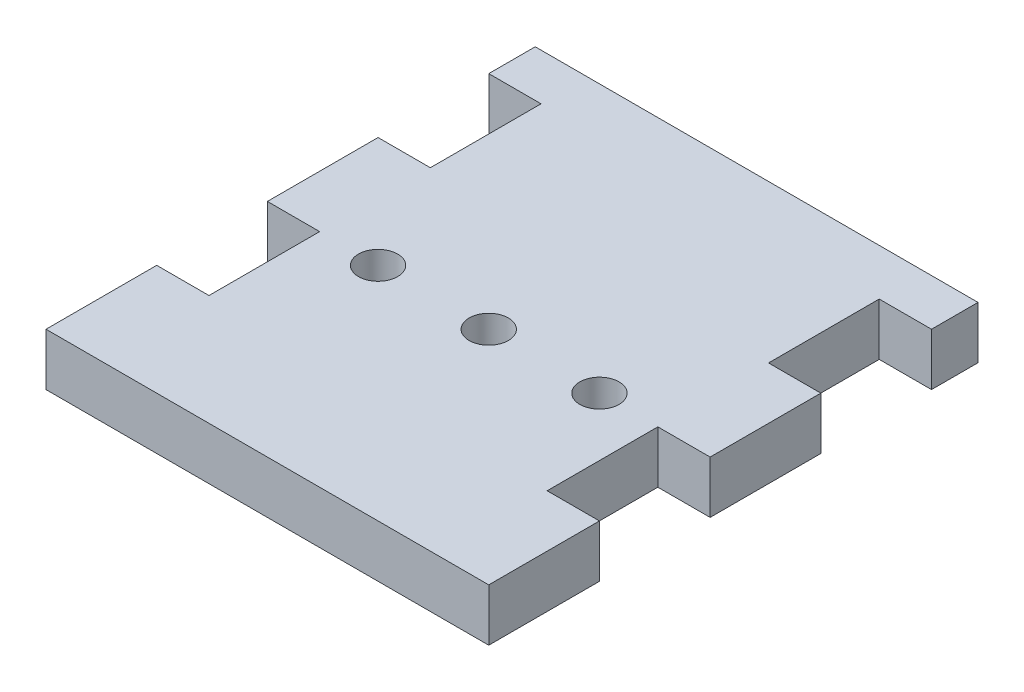
SolidWorks part; units mm, degrees
material "Custom Plastic"
ref_plane "Front Plane" through (0, 0, 0) normal (0, 0, 1) x (1, 0, 0)
ref_plane "Top Plane" through (0, 0, 0) normal (0, 1, 0) x (1, 0, 0)
ref_plane "Right Plane" through (0, 0, 0) normal (1, 0, 0) x (0, 0, -1)
sketch "Sketch1" plane through (0, 0, 0) normal (0, 1, 0) x (1, 0, 0)
  line L1 (25.4, -28.067) -> (-25.4, -28.067)
  line L2 (25.4, -28.067) -> (25.4, 28.067)
  line L3 (25.4, 28.067) -> (-25.4, 28.067)
  line L4 (-25.4, -28.067) -> (-25.4, 28.067)
  line L5 (25.4, -28.067) -> (-25.4, 28.067) construction
  line L6 (25.4, 28.067) -> (-25.4, -28.067) construction
  point P0 (0, 0)
  dimension "D1" = 56.134
  dimension "D2" = 50.8
extrude "Main" add sketch "Sketch1" along normal blind 6
sketch "Sketch2" plane through (0, 6, 0) normal (0, 1, 0) x (1, 0, 0)
  line L1 (-25.4, 28.067) -> (-25.4, -28.067) construction
  line L2 (-25.4, -15.367) -> (-19.4, -15.367)
  line L3 (-25.4, -15.367) -> (-25.4, -2.667)
  line L4 (-25.4, -2.667) -> (-19.4, -2.667)
  line L5 (-19.4, -15.367) -> (-19.4, -2.667)
  line L6 (-19.4, 10.033) -> (-19.4, -2.667) construction
  line L7 (-25.4, 10.033) -> (-19.4, 10.033)
  line L8 (-25.4, 10.033) -> (-25.4, 22.733)
  line L9 (-25.4, 22.733) -> (-19.4, 22.733)
  line L10 (-19.4, 10.033) -> (-19.4, 22.733)
  line L11 (-19.4, -15.367) -> (-19.4, -28.067) construction
  line L12 (-25.4, -28.067) -> (25.4, -28.067) construction
  line L13 (0, 28.067) -> (0, -28.067) construction
  line L14 (25.4, 28.067) -> (-25.4, 28.067) construction
  line L16 (19.4, -15.367) -> (19.4, -28.067) construction
  line L18 (19.4, 10.033) -> (19.4, -2.667) construction
  line L19 (19.4, 10.033) -> (19.4, 22.733)
  line L20 (25.4, 22.733) -> (19.4, 22.733)
  line L21 (25.4, 10.033) -> (25.4, 22.733)
  line L22 (25.4, 10.033) -> (19.4, 10.033)
  line L23 (19.4, -15.367) -> (19.4, -2.667)
  line L24 (25.4, -2.667) -> (19.4, -2.667)
  line L25 (25.4, -15.367) -> (25.4, -2.667)
  line L26 (25.4, -15.367) -> (19.4, -15.367)
  dimension "D1" = 6
  dimension "D2" = 12.7
extrude "Acrylic Mounts" cut sketch "Sketch2" against normal through all
sketch "Sketch3" plane through (0, 0, 0) normal (0, -1, 0) x (-1, 0, 0)
  line L0 (-12.7, -2.667) -> (12.7, -2.667) construction
  line L1 (12.7, -2.667) -> (19.4, -2.667) construction
  line L2 (19.4, -15.367) -> (19.4, -2.667) construction
  line L3 (-12.7, -2.667) -> (-19.4, -2.667) construction
  line L4 (-19.4, -2.667) -> (-19.4, -15.367) construction
  line L6 (19.4, -2.667) -> (25.4, -2.667) construction
  circle A2 centre (12.7, -2.667) radius 2.2479
  circle A3 centre (-12.7, -2.667) radius 2.2479
  circle A4 centre (0, -2.667) radius 2.2479
  dimension "D1" = 4.4958
  dimension "D2" = 12.7
extrude "Cut-Extrude1" cut sketch "Sketch3" against normal through all
